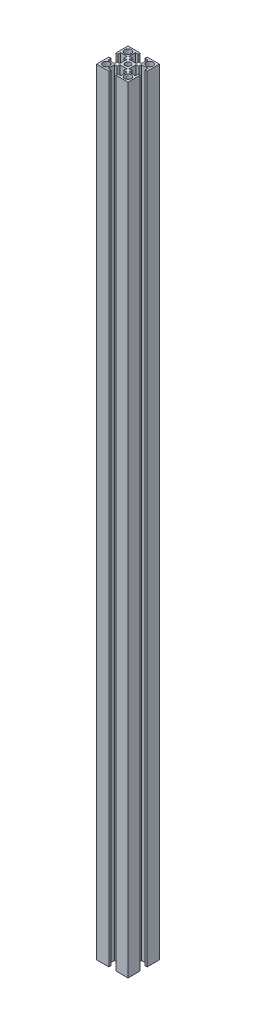
SolidWorks part; units mm, degrees
material "6061 合金"
ref_plane "前视基准面" through (0, 0, 0) normal (0, 0, 1) x (1, 0, 0)
ref_plane "上视基准面" through (0, 0, 0) normal (0, 1, 0) x (1, 0, 0)
ref_plane "右视基准面" through (0, 0, 0) normal (1, 0, 0) x (0, 0, -1)
other "Configuration Table"
sketch "草图1" plane through (0, 0, 0) normal (0, 1, 0) x (1, 0, 0)
  line L0 (-2.2, 10) -> (-2.2, 8.7)
  line L1 (-10, -10) -> (10, -10)
  line L2 (-10, -10) -> (-10, 10)
  line L3 (-10, 10) -> (10, 10)
  line L4 (10, -10) -> (10, 10)
  line L5 (-10, -10) -> (10, 10) construction
  line L6 (-10, 10) -> (10, -10) construction
  line L7 (-2.2, 8.7) -> (-4.05, 8.7)
  line L8 (-4.05, 8.7) -> (-4.05, 4.7)
  line L9 (-4.05, 4.7) -> (-2.2, 4.7)
  line L10 (-2.2, 4.7) -> (-2.2, 2.95)
  line L11 (0, 818.9931) -> (0, -818.9931) construction
  line L12 (-818.9931, 0) -> (818.9931, 0) construction
  line L13 (2.2, 4.7) -> (2.2, 2.95)
  line L14 (4.05, 4.7) -> (2.2, 4.7)
  line L15 (4.05, 8.7) -> (4.05, 4.7)
  line L16 (2.2, 8.7) -> (4.05, 8.7)
  line L17 (2.2, 10) -> (2.2, 8.7)
  line L18 (-2.2, 2.95) -> (2.2, 2.95)
  line L19 (8.7, 4.05) -> (4.7, 4.05)
  line L20 (2.95, 2.95) -> (-2.95, 2.95)
  line L21 (2.95, 2.95) -> (2.95, -2.95)
  line L22 (2.95, -2.95) -> (-2.95, -2.95)
  line L23 (-2.95, 2.95) -> (-2.95, -2.95)
  line L24 (2.95, 2.95) -> (-2.95, -2.95) construction
  line L25 (2.95, -2.95) -> (-2.95, 2.95) construction
  line L26 (4.7, 4.05) -> (4.7, 2.2)
  line L27 (4.7, 2.2) -> (2.95, 2.2)
  line L28 (10, 2.2) -> (8.7, 2.2)
  line L29 (8.7, 2.2) -> (8.7, 4.05)
  line L30 (10, -2.2) -> (8.7, -2.2)
  line L31 (8.7, -2.2) -> (8.7, -4.05)
  line L32 (8.7, -4.05) -> (4.7, -4.05)
  line L33 (4.7, -4.05) -> (4.7, -2.2)
  line L34 (4.7, -2.2) -> (2.95, -2.2)
  line L35 (4.05, -8.7) -> (4.05, -4.7)
  line L36 (4.05, -4.7) -> (2.2, -4.7)
  line L37 (2.2, -4.7) -> (2.2, -2.95)
  line L38 (2.2, -10) -> (2.2, -8.7)
  line L39 (2.2, -8.7) -> (4.05, -8.7)
  line L40 (-2.2, -10) -> (-2.2, -8.7)
  line L41 (-2.2, -8.7) -> (-4.05, -8.7)
  line L42 (-4.05, -8.7) -> (-4.05, -4.7)
  line L43 (-4.05, -4.7) -> (-2.2, -4.7)
  line L44 (-2.2, -4.7) -> (-2.2, -2.95)
  line L45 (-8.7, -4.05) -> (-4.7, -4.05)
  line L46 (-4.7, -4.05) -> (-4.7, -2.2)
  line L47 (-4.7, -2.2) -> (-2.95, -2.2)
  line L48 (-10, -2.2) -> (-8.7, -2.2)
  line L49 (-8.7, -2.2) -> (-8.7, -4.05)
  line L50 (-10, 2.2) -> (-8.7, 2.2)
  line L51 (-8.7, 2.2) -> (-8.7, 4.05)
  line L52 (-8.7, 4.05) -> (-4.7, 4.05)
  line L53 (-4.7, 4.05) -> (-4.7, 2.2)
  line L54 (-4.7, 2.2) -> (-2.95, 2.2)
  circle A0 centre (0, 0) radius 1.75
  circle A1 centre (6.9, 6.9) radius 2.15
  circle A2 centre (6.9, -6.9) radius 2.15
  circle A3 centre (-6.9, -6.9) radius 2.15
  circle A4 centre (-6.9, 6.9) radius 2.15
  point P74 (0, 0)
  dimension "D2" = 3.5
  dimension "D10" = 4.3
  dimension "D1" = 20
  dimension "D3" = 2.2
  dimension "D4" = 5.9
  dimension "D5" = 5.3
  dimension "D6" = 1.3
  dimension "D7" = 8.1
  dimension "D8" = 1.75
  dimension "D9" = 6.9
  dimension "D11" = 4
extrude "凸台-拉伸1" add sketch "草图1" against normal blind 495 contours L53 L54 L23 L20 L10 L9 L8 L7 L0 L3 L2 L50 L51 L52 A4 | L20 L23 L22 L21 L18 A0 | L49 L48 L2 L1 L40 L41 L42 L43 L44 L22 L23 L47 L46 L45 A3 | L39 L38 L1 L4 L30 L31 L32 L33 L34 L21 L22 L37 L36 L35 A2 | L29 L28 L4 L3 L17 L16 L15 L14 L13 L20 L21 L27 L26 L19 A1
sketch "草图2" plane through (-10, 0, 0) normal (-1, 0, 0) x (0, 0, 1)
  line L0 (-10, -247.5) -> (10, -247.5) construction
  line L1 (10, -495) -> (10, 0) construction
  line L2 (-10, -495) -> (-10, 0) construction
  circle A0 centre (0, -247.5) radius 2.5
  circle A1 centre (0, -67.5) radius 2.5
  circle A2 centre (0, -427.5) radius 2.5
  dimension "D2" = 5
  dimension "D3" = 180
  dimension "D1" = 180
  dimension "D4" = 180
extrude "切除-拉伸1" [suppressed] cut sketch "草图2" against normal through all
sketch "草图3" [suppressed] plane through (10, 0, 0) normal (1, 0, 0) x (0, 0, -1)
  circle A0 centre (0, -67.5) radius 4.5
  circle A1 centre (0, -247.5) radius 4.5
  circle A2 centre (0, -427.5) radius 4.5
  dimension "D1" = 9
extrude "切除-拉伸2" [suppressed] cut sketch "草图3" against normal up to surface (7.05 mm away)
